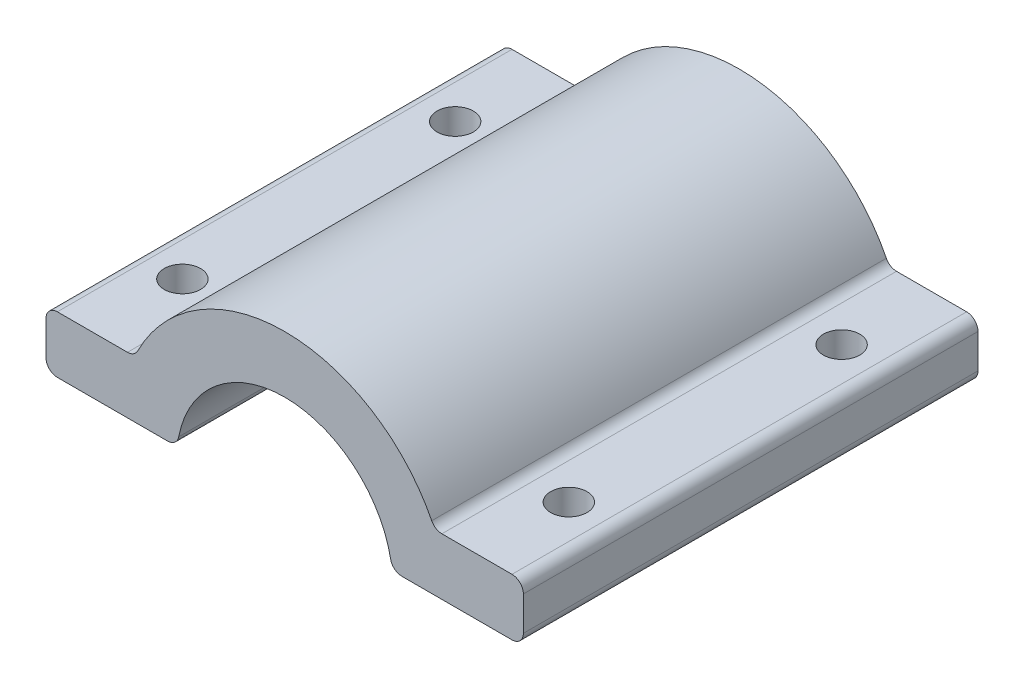
SolidWorks part; units mm, degrees
ref_plane "前视基准面" through (0, 0, 0) normal (0, 0, 1) x (1, 0, 0)
ref_plane "上视基准面" through (0, 0, 0) normal (0, 1, 0) x (1, 0, 0)
ref_plane "右视基准面" through (0, 0, 0) normal (1, 0, 0) x (0, 0, -1)
other "Configuration Table"
sketch "草图1" plane through (0, 0, 0) normal (0, 0, 1) x (1, 0, 0)
  line L0 (-14.4655, 1) -> (-10.3078, 1)
  line L1 (10.3078, 1) -> (14.4655, 1)
  line L2 (-20, 6) -> (-13.8293, 6)
  line L4 (-21, 5) -> (-21, 2)
  line L5 (-20, 1) -> (-14.4655, 1)
  line L6 (0, -55) -> (0, 55) construction
  line L7 (20, 1) -> (14.4655, 1)
  line L8 (21, 5) -> (21, 2)
  line L9 (20, 6) -> (13.8293, 6)
  arc A0 (9.3261, 1.8095) -> (-9.3261, 1.8095) centre (0, 0) ccw
  arc A1 (12.9371, 6.5484) -> (-12.9371, 6.5484) centre (0, 0) ccw
  arc A2 (12.9371, 6.5484) -> (13.8293, 6) centre (13.8293, 7) ccw
  arc A3 (-13.8293, 6) -> (-12.9371, 6.5484) centre (-13.8293, 7) ccw
  arc A4 (9.3261, 1.8095) -> (10.3078, 1) centre (10.3078, 2) ccw
  arc A5 (-9.3261, 1.8095) -> (-10.3078, 1) centre (-10.3078, 2) cw
  arc A6 (-20, 6) -> (-21, 5) centre (-20, 5) ccw
  arc A7 (-21, 2) -> (-20, 1) centre (-20, 2) ccw
  arc A8 (21, 5) -> (20, 6) centre (20, 5) ccw
  arc A9 (20, 1) -> (21, 2) centre (20, 2) ccw
  point P10 (-14.2697, 1)
  point P17 (13.2004, 6)
  point P20 (-13.2004, 6)
  point P23 (9.4472, 1)
  point P28 (-21, 6)
  point P31 (-21, 1)
  point P34 (21, 6)
  point P37 (21, 1)
  dimension "D1" = 19
  dimension "D3" = 29
  dimension "D6" = 1
  dimension "D7" = 1
  dimension "D8" = 1
  dimension "D9" = 1
  dimension "D2" = 1
  dimension "D4" = 5
  dimension "D5" = 21
extrude "凸台-拉伸1" add sketch "草图1" along normal blind 40
sketch "草图2" plane through (0, 6, 0) normal (0, 1, 0) x (1, 0, 0)
  line L0 (-21, -40) -> (-21, 0) construction
  line L1 (-13.8293, 0) -> (-20, 0) construction
  line L2 (21, -40) -> (21, 0) construction
  line L3 (-13.8293, -40) -> (-20, -40) construction
  circle A0 centre (-17, -8) radius 1.6
  circle A1 centre (17, -8) radius 1.6
  circle A2 centre (17, -32) radius 1.6
  circle A3 centre (-17, -32) radius 1.6
  dimension "D1" = 3.2
  dimension "D2" = 4
  dimension "D3" = 8
  dimension "D6" = 4
  dimension "D7" = 8
  dimension "D8" = 4
  dimension "D4" = 2
  dimension "D5" = 2
extrude "切除-拉伸1" cut sketch "草图2" against normal blind 40
